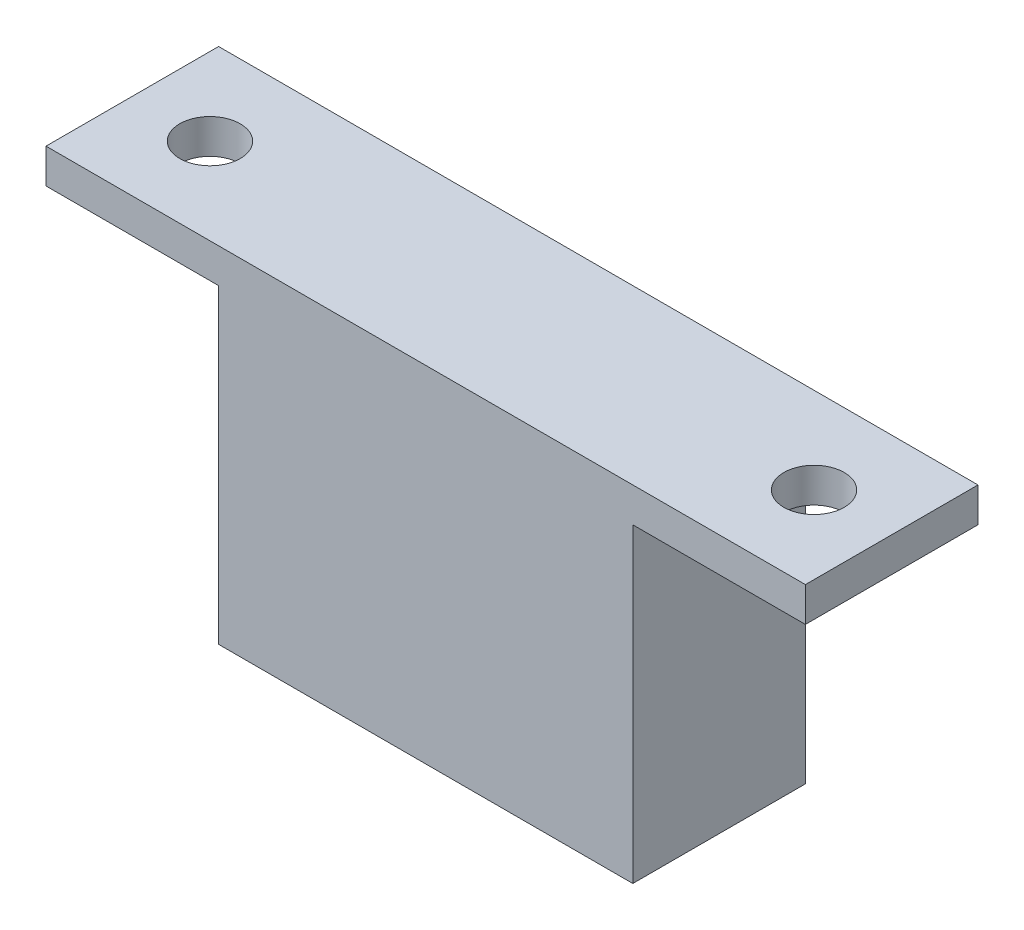
SolidWorks part; units mm, degrees
ref_plane "Plano frontal" through (0, 0, 0) normal (0, 0, 1) x (1, 0, 0)
ref_plane "Plano superior" through (0, 0, 0) normal (0, 1, 0) x (1, 0, 0)
ref_plane "Plano direito" through (0, 0, 0) normal (1, 0, 0) x (0, 0, -1)
sketch "Esboço1" plane through (0, 0, 0) normal (0, 0, 1) x (1, 0, 0)
  line L0 (-12, 5) -> (-22, 5)
  line L1 (-12, 5) -> (12, 5)
  line L2 (-12, 3) -> (-12, -15)
  line L3 (-12, -15) -> (12, -15)
  line L4 (12, 3) -> (12, -15)
  line L7 (-22, 5) -> (-22, 3)
  line L8 (-22, 3) -> (-12, 3)
  line L9 (0, 5) -> (0, -15) construction
  line L10 (22, 5) -> (22, 3)
  line L11 (12, 5) -> (22, 5)
  line L12 (22, 3) -> (12, 3)
  point P0 (0, 0)
  dimension "D1" = 24
  dimension "D2" = 20
  dimension "D3" = 10
  dimension "D4" = 2
extrude "Ressalto-extrusão1" add sketch "Esboço1" along normal blind 10
sketch "Esboço2" plane through (0, 5, 0) normal (0, 1, 0) x (1, 0, 0)
  line L0 (0, 0) -> (0, -10) construction
  line L1 (22, 0) -> (-22, 0) construction
  line L2 (22, -10) -> (-22, -10) construction
  line L3 (-22, -10) -> (-22, 0) construction
  circle A0 centre (-17.5, -5) radius 1.75
  circle A1 centre (17.5, -5) radius 1.75
  point P8 (0, 0)
  point P11 (-22, -5)
  point P14 (-17.5, -5)
  dimension "D2" = 3.5
  dimension "D1" = 35
extrude "Corte-extrusão1" cut sketch "Esboço2" against normal blind 10
